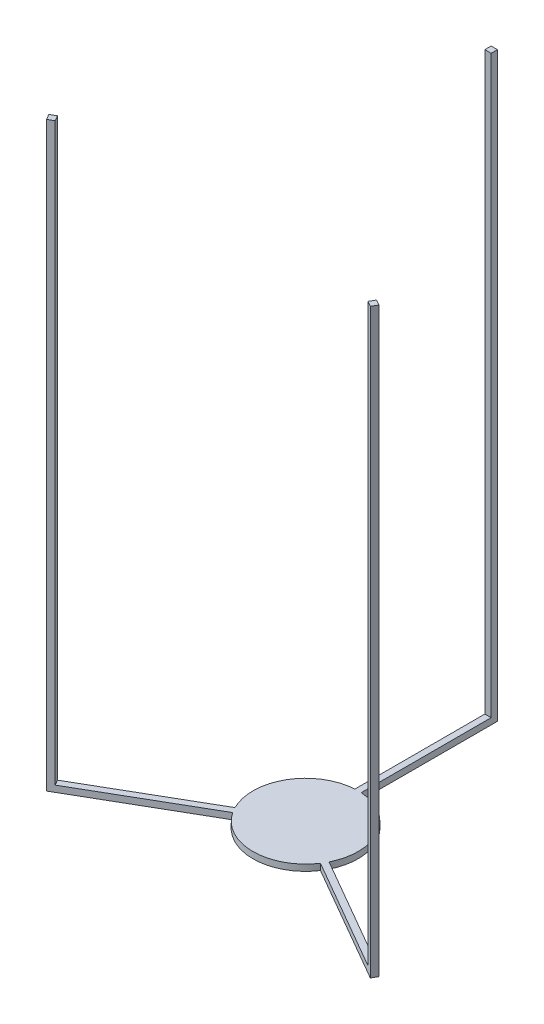
SolidWorks part; units mm, degrees
ref_plane "Plan de face" through (0, 0, 0) normal (0, 0, 1) x (1, 0, 0)
ref_plane "Plan de dessus" through (0, 0, 0) normal (0, 1, 0) x (1, 0, 0)
ref_plane "Plan de droite" through (0, 0, 0) normal (1, 0, 0) x (0, 0, -1)
sketch3d "Esquisse3D1"
  line L0 (0, 0, 0) -> (0, 0, -176.45)
  line L1 (0, 0, -176.45) -> (0, 550, -176.45)
  dimension "D1" = 176.45
  dimension "D2" = 550
  dimension "D3" = 90
sketch "Esquisse2" plane through (0, 0, 0) normal (0, 0, 1) x (1, 0, 0)
  line L0 (-3, 0) -> (3, 0) construction
  line L1 (-3, 3) -> (3, 3)
  line L2 (-3, 3) -> (-3, -3)
  line L3 (-3, -3) -> (3, -3)
  line L4 (3, 3) -> (3, -3)
  line L5 (0, 3) -> (0, -3) construction
  dimension "D1" = 6
  dimension "D2" = 6
sweep "Balayage2" add profiles "Esquisse2" path "Esquisse3D1"
sketch "Esquisse3" plane through (0, 0, 0) normal (0, 1, 0) x (1, 0, 0)
  circle A0 centre (0, 0) radius 50
  dimension "D1" = 100
extrude "Boss.-Extru.1" add sketch "Esquisse3" along normal mid plane 6
pattern_circular "Répétition circulaire1" count 3 over 360 about axis through (0, 0, 0) along (0, 1, 0) of "Balayage2"
